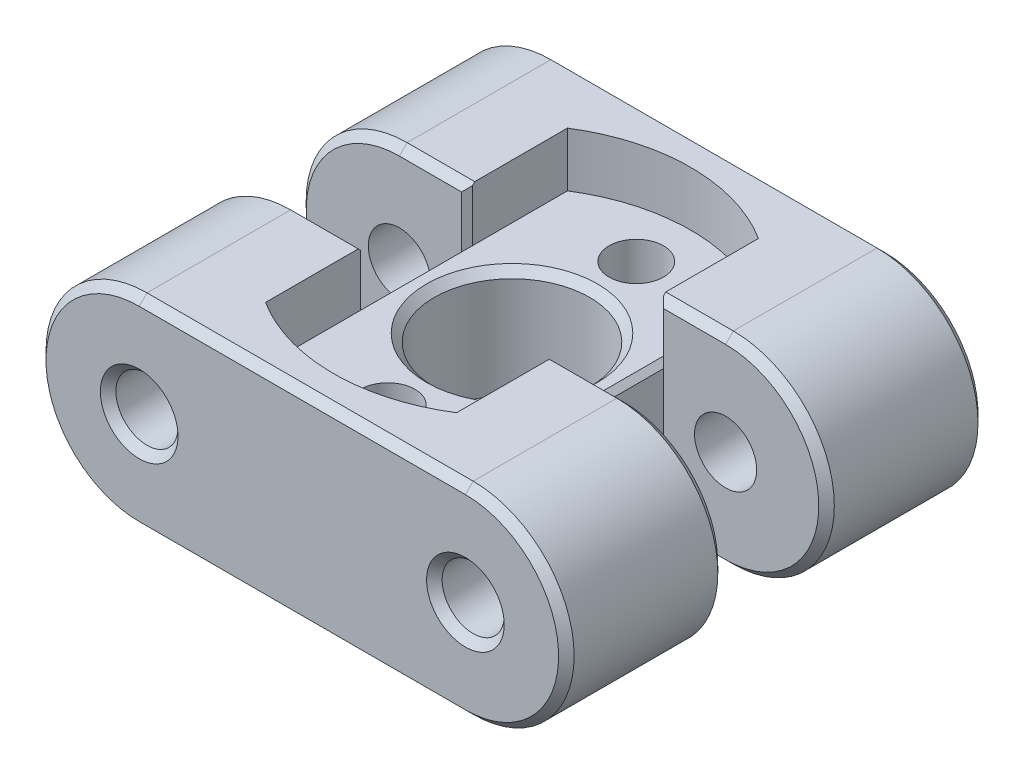
SolidWorks part; units mm, degrees
material "1023 Carbon Steel Sheet (SS)"
ref_plane "Front Plane" through (0, 0, 0) normal (0, 0, 1) x (1, 0, 0)
ref_plane "Top Plane" through (0, 0, 0) normal (0, 1, 0) x (1, 0, 0)
ref_plane "Right Plane" through (0, 0, 0) normal (1, 0, 0) x (0, 0, -1)
sketch "Sketch1" plane through (0, 0, 0) normal (0, 1, 0) x (1, 0, 0)
  line L1 (-10.5, -13.5) -> (10.5, -13.5)
  line L2 (-10.5, -13.5) -> (-10.5, 13.5)
  line L3 (-10.5, 13.5) -> (10.5, 13.5)
  line L4 (10.5, -13.5) -> (10.5, 13.5)
  line L5 (-10.5, -13.5) -> (10.5, 13.5) construction
  line L6 (-10.5, 13.5) -> (10.5, -13.5) construction
  point P0 (0, 0)
  dimension "D1" = 27
  dimension "D2" = 21
extrude "Boss-Extrude1" add sketch "Sketch1" along normal blind 13
sketch "Sketch8" plane through (0, 0, -13.5) normal (0, 0, -1) x (-1, 0, 0)
  line L0 (-10.5, 13) -> (-10.5, 0) construction
  line L1 (10.5, 13) -> (10.5, 0) construction
  circle A0 centre (-10.5, 6.5) radius 6.5
  circle A1 centre (10.5, 6.5) radius 6.5
extrude "Boss-Extrude2" add sketch "Sketch8" against normal up to surface (27 mm away) up to face at (0, 6.5, 13.5)
sketch "Sketch2" plane through (0, 13, 0) normal (0, 1, 0) x (1, 0, 0)
  circle A0 centre (0, 0) radius 5
  dimension "D1" = 10
extrude "Cut-Extrude1" cut sketch "Sketch2" against normal blind 13
sketch "Sketch3" plane through (0, 13, 0) normal (0, 1, 0) x (1, 0, 0)
  line L1 (6.5, 3.25) -> (28.0017, 3.25)
  line L2 (6.5, 3.25) -> (6.5, -3.25)
  line L3 (6.5, -3.25) -> (28.0017, -3.25)
  line L4 (28.0017, 3.25) -> (28.0017, -3.25)
  line L5 (6.5, 3.25) -> (28.0017, -3.25) construction
  line L6 (6.5, -3.25) -> (28.0017, 3.25) construction
  line L7 (-6.5, 0) -> (6.5, 0) construction
  line L8 (0, 0) -> (0, 13.5) construction
  line L9 (10.5, 13.5) -> (-10.5, 13.5) construction
  line L10 (-6.5, -3.25) -> (-28.0017, 3.25) construction
  line L11 (-6.5, 3.25) -> (-28.0017, -3.25) construction
  line L12 (-28.0017, 3.25) -> (-28.0017, -3.25)
  line L13 (-6.5, -3.25) -> (-28.0017, -3.25)
  line L14 (-6.5, 3.25) -> (-6.5, -3.25)
  line L15 (-6.5, 3.25) -> (-28.0017, 3.25)
  point P0 (17.2509, 0)
  point P18 (-17.2509, 0)
  dimension "D1" = 13
  dimension "D2" = 6.5
extrude "Cut-Extrude2" cut sketch "Sketch3" against normal blind 13
sketch "Sketch7" plane through (0, 13, 0) normal (0, 1, 0) x (1, 0, 0)
  line L1 (-6.5, -3.25) -> (6.5, -3.25)
  line L2 (-6.5, -3.25) -> (-6.5, 3.25)
  line L3 (-6.5, 3.25) -> (6.5, 3.25)
  line L4 (6.5, -3.25) -> (6.5, 3.25)
  line L5 (-6.5, -3.25) -> (6.5, 3.25) construction
  line L6 (-6.5, 3.25) -> (6.5, -3.25) construction
  point P0 (0, 0)
extrude "Cut-Extrude7" cut sketch "Sketch7" against normal blind 3.5
sketch "Sketch4" plane through (0, 0, 13.5) normal (0, 0, 1) x (1, 0, 0)
  line L0 (-10.5, 6.5) -> (0, 6.5) construction
  line L1 (0, 6.5) -> (0, 0) construction
  line L2 (0, 6.5) -> (10.5, 6.5) construction
  line L3 (0, 6.5) -> (0, 13) construction
  line L4 (-10.5, 13) -> (10.5, 13) construction
  circle A0 centre (-10.5, 6.5) radius 2
  circle A1 centre (10.5, 6.5) radius 2
  dimension "D2" = 4
  dimension "D1" = 21
extrude "Cut-Extrude3" cut sketch "Sketch4" against normal blind 35
sketch "Sketch5" plane through (0, 13, 0) normal (0, 1, 0) x (1, 0, 0)
  line L2 (-6.15, 9.7174) -> (-6.15, -9.7174)
  line L4 (6.15, 9.7174) -> (6.15, -9.7174)
  line L5 (-6.15, 9.7174) -> (6.15, -9.7174) construction
  line L6 (-6.15, -9.7174) -> (6.15, 9.7174) construction
  arc A0 (6.15, 9.7174) -> (-6.15, 9.7174) centre (0, 0) ccw
  arc A1 (-6.15, -9.7174) -> (6.15, -9.7174) centre (0, 0) ccw
  dimension "D1" = 23
  dimension "D2" = 12.3
extrude "Cut-Extrude4" cut sketch "Sketch5" against normal blind 3.5
sketch "Sketch6" plane through (0, 9.5, 0) normal (0, 1, 0) x (1, 0, 0)
  line L0 (0, -8) -> (0, 8) construction
  circle A0 centre (0, 8) radius 1.75
  circle A1 centre (0, -8) radius 1.75
  point P5 (0, 0)
  dimension "D1" = 3.5
  dimension "D2" = 16
extrude "Cut-Extrude5" cut sketch "Sketch6" against normal blind 6
chamfer "Chamfer1" distance 0.5 angle 45 26 edges at (12.5, 6.5, 13.5) (-8.5, 6.5, 13.5) (12.5, 6.5, -13.5) (-8.5, 6.5, -13.5) (0, 13, 13.5) (0, 0, 13.5) (0, 13, -13.5) (8.325, 13, -3.25) (8.325, 13, 3.25) (8.5, 0, 3.25) (8.5, 0, -3.25) (0, 0, -13.5) (-8.5, 0, 3.25) (-8.5, 0, -3.25) (-8.325, 13, 3.25) (-8.325, 13, -3.25) (0, 9.5, -5) (0, 0, 5) (17, 6.5, 13.5) (-17, 6.5, 13.5) (17, 6.5, -3.25) (17, 6.5, -13.5) (17, 6.5, 3.25) (-17, 6.5, -3.25) (-17, 6.5, -13.5) (-17, 6.5, 3.25)
chamfer "Chamfer2" distance 0.35 angle 45 4 edges at (6.15, 11, 3.25) (6.15, 11, -3.25) (-6.15, 11, -3.25) (-6.15, 11, 3.25)
chamfer "Chamfer3" distance 0.35 angle 45 4 edges at (6.5, 9.5, 0) (-6.5, 9.5, 0) (-6.5, 0, 0) (6.5, 0, 0)
sketch "Sketch9" plane through (0, 0, 0) normal (0, -1, 0) x (1, 0, 0)
  circle A0 centre (0, 0) radius 10
  dimension "D1" = 20
extrude "Cut-Extrude8" cut sketch "Sketch9" against normal blind 2.5
sketch "Sketch10" plane through (0, 2.5, 0) normal (0, -1, 0) x (1, 0, 0)
  circle A0 centre (0, 0) radius 8
  dimension "D1" = 16
